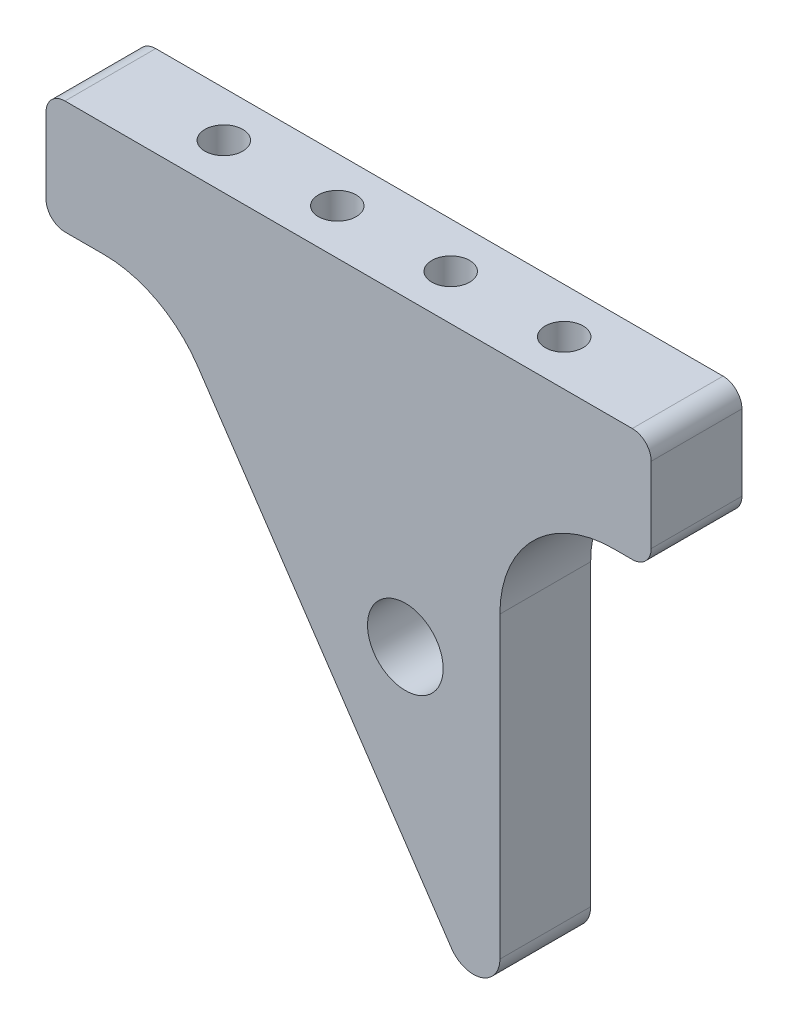
SolidWorks part; units mm, degrees
ref_plane "前视基准面" through (0, 0, 0) normal (0, 0, 1) x (1, 0, 0)
ref_plane "上视基准面" through (0, 0, 0) normal (0, 1, 0) x (1, 0, 0)
ref_plane "右视基准面" through (0, 0, 0) normal (1, 0, 0) x (0, 0, -1)
sketch "草图1" plane through (0, 0, 0) normal (0, 0, 1) x (1, 0, 0)
  line L0 (12.5, 0) -> (12.5, -29.5)
  line L1 (-10.3712, -6.9777) -> (6.0961, -31.4537)
  line L2 (-27.427, 18.3732) -> (-10.3712, -6.9777)
  line L3 (12.5, 0) -> (12.5, 10)
  line L8 (-12.5, 0) -> (-12.5, 10) construction
  line L9 (-39.8725, 25) -> (-45, 25)
  line L10 (-47.5, 27.5) -> (-47.5, 37.5)
  line L11 (-45, 40) -> (30, 40)
  line L12 (32.5, 37.5) -> (32.5, 27.5)
  line L13 (30, 25) -> (27.5, 25)
  line L14 (-27.5, 25) -> (-31.8855, 25) construction
  arc A0 (-12.5, 0) -> (-10.3712, -6.9777) centre (0, 0) ccw construction
  arc A1 (12.5, -29.5) -> (6.0961, -31.4537) centre (9, -29.5) cw
  arc A2 (-10.3712, -6.9777) -> (12.5, 0) centre (0, 0) ccw construction
  circle A7 centre (0, 0) radius 5
  arc A8 (12.5, 0) -> (-12.5, 0) centre (0, 0) ccw construction
  arc A9 (30, 40) -> (32.5, 37.5) centre (30, 37.5) cw
  arc A10 (32.5, 27.5) -> (30, 25) centre (30, 27.5) cw
  arc A11 (-45, 25) -> (-47.5, 27.5) centre (-45, 27.5) cw
  arc A12 (-45, 40) -> (-47.5, 37.5) centre (-45, 37.5) ccw
  arc A13 (27.5, 25) -> (12.5, 10) centre (27.5, 10) ccw
  arc A14 (-12.5, 10) -> (-27.5, 25) centre (-27.5, 10) ccw construction
  arc A15 (-39.8725, 25) -> (-27.427, 18.3732) centre (-39.8725, 10) cw
  point P6 (0, -12.5)
  point P18 (32.5, 40)
  point P21 (32.5, 25)
  point P27 (-47.5, 40)
  point P30 (12.5, 25)
  point P33 (-12.5, 25)
  point P34 (-31.8469, 25)
  dimension "D1" = 25
  dimension "D2" = 3.5
  dimension "D4" = 80
  dimension "D5" = 10
  dimension "D9" = 2.5
  dimension "D10" = 15
  dimension "D11" = 15
  dimension "D3" = 17
  dimension "D6" = 20
  dimension "D7" = 15
  dimension "D8" = 25
extrude "凸台-拉伸1" add sketch "草图1" along normal blind 12
sketch "草图2" plane through (0, 40, 0) normal (0, 1, 0) x (1, 0, 0)
  line L0 (-45, -12) -> (-45, 0) construction
  line L1 (-30, -6) -> (-15, -6) construction
  line L2 (30, -12) -> (-45, -12) construction
  circle A0 centre (-30, -6) radius 2.5
  circle A1 centre (-15, -6) radius 2.5
  circle A2 centre (0, -6) radius 2.5
  circle A3 centre (15, -6) radius 2.5
  dimension "D1" = 5
  dimension "D2" = 15
  dimension "D4" = 15
  dimension "D5" = 6
  dimension "D3" = 4
extrude "切除-拉伸1" cut sketch "草图2" against normal blind 10
